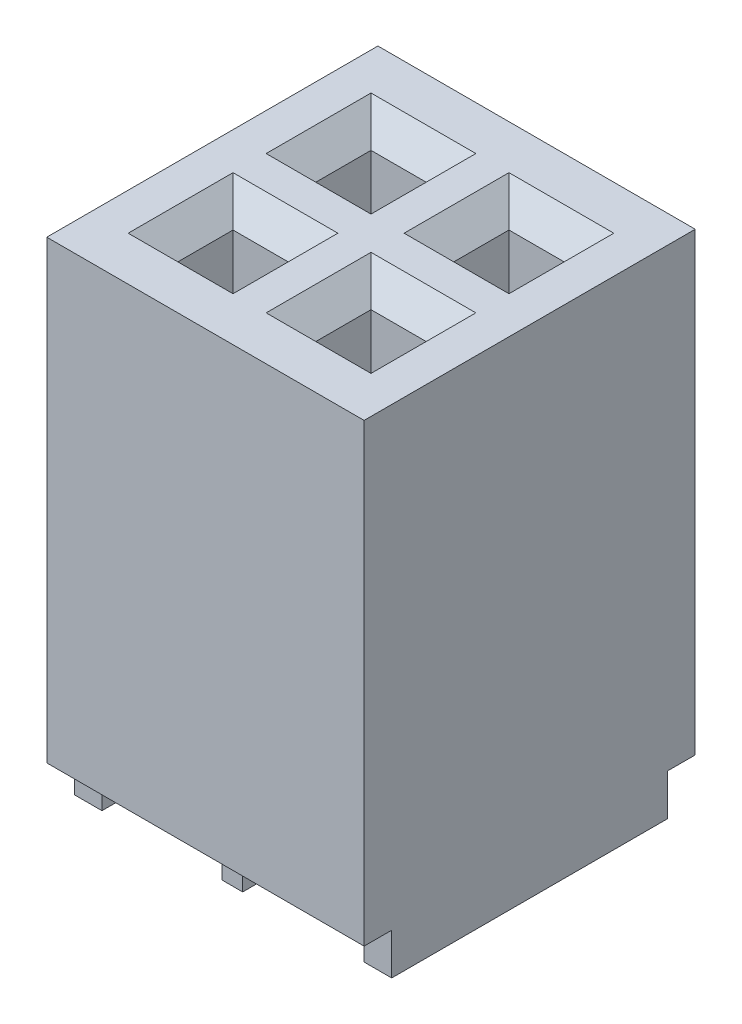
SolidWorks part; units mm, degrees
ref_plane "正面" through (0, 0, 0) normal (0, 0, 1) x (1, 0, 0)
ref_plane "平面" through (0, 0, 0) normal (0, 1, 0) x (1, 0, 0)
ref_plane "右側面" through (0, 0, 0) normal (1, 0, 0) x (0, 0, -1)
ref_plane "平面1" through (1.4605, 0, 0) normal (1, 0, 0) x (0, 0, -1)
sketch "ｽｹｯﾁ1" plane through (1.4605, 0, 0) normal (1, 0, 0) x (0, 0, -1)
  line L0 (-1.524, 4.572) -> (-1.524, 0.381)
  line L1 (-1.524, 0.381) -> (1.524, 0.381)
  line L2 (1.524, 0.381) -> (1.524, 4.572)
  line L3 (1.524, 4.572) -> (-1.524, 4.572)
extrude "ﾎﾞｽ - 押し出し1" add sketch "ｽｹｯﾁ1" against normal blind 2.921
sketch "ｽｹｯﾁ2" plane through (0, 0.381, 0) normal (0, -1, 0) x (1, 0, 0)
  line L0 (1.2065, -1.27) -> (1.2065, 1.27)
  line L1 (1.2065, 1.27) -> (1.4605, 1.27)
  line L2 (1.4605, 1.27) -> (1.4605, -1.27)
  line L3 (1.4605, -1.27) -> (1.2065, -1.27)
extrude "ﾎﾞｽ - 押し出し2" add sketch "ｽｹｯﾁ2" along normal blind 0.381
sketch "ｽｹｯﾁ3" plane through (0, 0.381, 0) normal (0, -1, 0) x (1, 0, 0)
  line L0 (-1.4605, -1.27) -> (-1.4605, 1.27)
  line L1 (-1.4605, 1.27) -> (-1.2065, 1.27)
  line L2 (-1.2065, 1.27) -> (-1.2065, -1.27)
  line L3 (-1.2065, -1.27) -> (-1.4605, -1.27)
extrude "ﾎﾞｽ - 押し出し3" add sketch "ｽｹｯﾁ3" along normal blind 0.381
sketch "ｽｹｯﾁ4" plane through (0, 0.381, 0) normal (0, -1, 0) x (1, 0, 0)
  line L0 (-0.1016, -1.27) -> (-0.1016, 1.27)
  line L1 (-0.1016, 1.27) -> (0.0889, 1.27)
  line L2 (0.0889, 1.27) -> (0.0889, -1.27)
  line L3 (0.0889, -1.27) -> (-0.1016, -1.27)
extrude "ﾎﾞｽ - 押し出し4" add sketch "ｽｹｯﾁ4" along normal blind 0.381
sketch "ｽｹｯﾁ5" plane through (0, 4.572, 0) normal (0, 1, 0) x (-1, 0, 0)
  line L0 (0.889, 0.381) -> (0.889, 0.889)
  line L1 (0.889, 0.889) -> (0.381, 0.889)
  line L2 (0.381, 0.889) -> (0.381, 0.381)
  line L3 (0.381, 0.381) -> (0.889, 0.381)
extrude "ｶｯﾄ - 押し出し1" cut sketch "ｽｹｯﾁ5" against normal blind 3.302
sketch "ｽｹｯﾁ6" plane through (0, 4.572, 0) normal (0, 1, 0) x (-1, 0, 0)
  line L0 (-0.381, 0.381) -> (-0.381, 0.889)
  line L1 (-0.381, 0.889) -> (-0.889, 0.889)
  line L2 (-0.889, 0.889) -> (-0.889, 0.381)
  line L3 (-0.889, 0.381) -> (-0.381, 0.381)
extrude "ｶｯﾄ - 押し出し2" cut sketch "ｽｹｯﾁ6" against normal blind 3.302
sketch "ｽｹｯﾁ7" plane through (0, 4.572, 0) normal (0, 1, 0) x (-1, 0, 0)
  line L0 (0.889, -0.889) -> (0.889, -0.381)
  line L1 (0.889, -0.381) -> (0.381, -0.381)
  line L2 (0.381, -0.381) -> (0.381, -0.889)
  line L3 (0.381, -0.889) -> (0.889, -0.889)
extrude "ｶｯﾄ - 押し出し3" cut sketch "ｽｹｯﾁ7" against normal blind 3.302
sketch "ｽｹｯﾁ8" plane through (0, 4.572, 0) normal (0, 1, 0) x (-1, 0, 0)
  line L0 (-0.381, -0.889) -> (-0.381, -0.381)
  line L1 (-0.381, -0.381) -> (-0.889, -0.381)
  line L2 (-0.889, -0.381) -> (-0.889, -0.889)
  line L3 (-0.889, -0.889) -> (-0.381, -0.889)
extrude "ｶｯﾄ - 押し出し4" cut sketch "ｽｹｯﾁ8" against normal blind 3.302
chamfer "面取り1" distance 0.2286 angle 45 16 edges at (0.635, 4.572, -0.889) (0.381, 4.572, -0.635) (0.889, 4.572, -0.635) (0.635, 4.572, -0.381) (-0.635, 4.572, -0.889) (-0.381, 4.572, -0.635) (-0.889, 4.572, -0.635) (-0.635, 4.572, -0.381) (-0.635, 4.572, 0.889) (-0.889, 4.572, 0.635) (-0.381, 4.572, 0.635) (-0.635, 4.572, 0.381) (0.889, 4.572, 0.635) (0.635, 4.572, 0.889) (0.635, 4.572, 0.381) (0.381, 4.572, 0.635)
